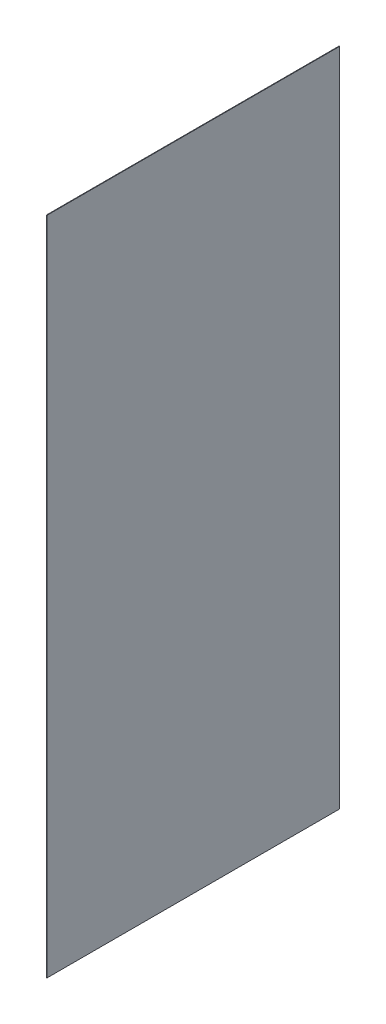
SolidWorks part; units mm, degrees
ref_plane "Front Plane" through (0, 0, 0) normal (0, 0, 1) x (1, 0, 0)
ref_plane "Top Plane" through (0, 0, 0) normal (0, 1, 0) x (1, 0, 0)
ref_plane "Right Plane" through (0, 0, 0) normal (1, 0, 0) x (0, 0, -1)
other "Configuration Table"
sketch "Sketch1" plane through (0, 0, 0) normal (0, 0, 1) x (1, 0, 0)
  line L1 (698.5, 120) -> (700, 120)
  line L2 (698.5, 120) -> (698.5, 1970)
  line L3 (698.5, 1970) -> (700, 1970)
  line L4 (700, 120) -> (700, 1970)
extrude "OVEN_dis_yan_sag_1" add sketch "Sketch1" against normal blind 820 separate body
